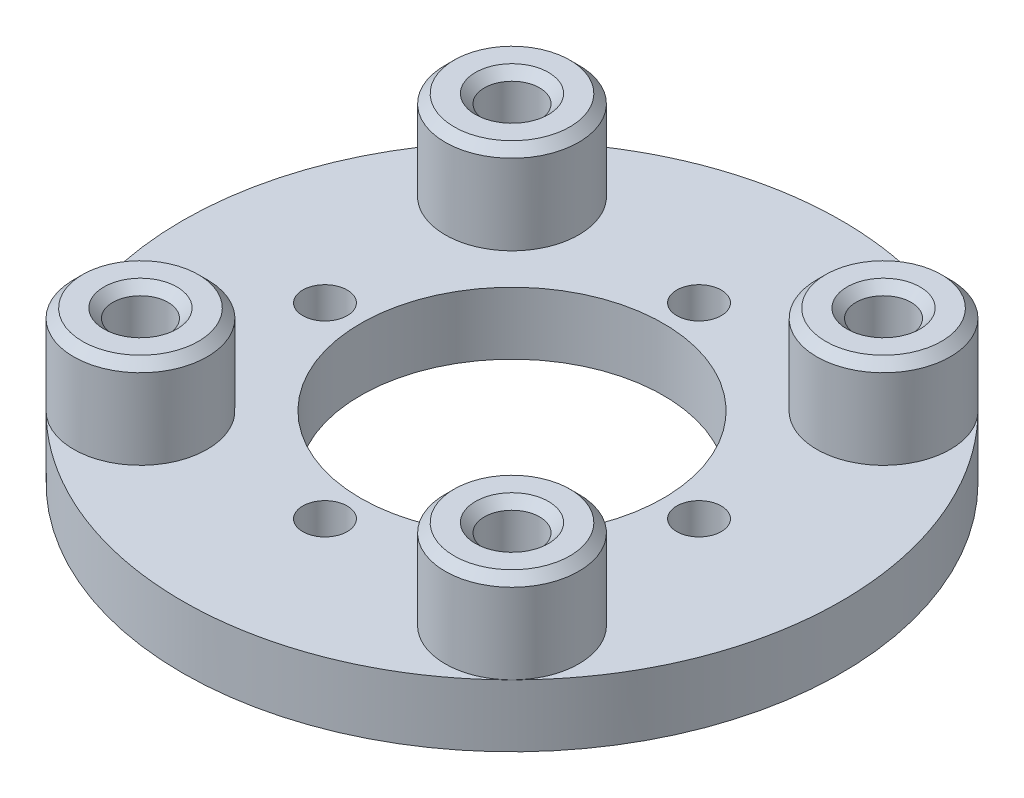
SolidWorks part; units mm, degrees
ref_plane "Front" through (0, 0, 0) normal (0, 0, 1) x (1, 0, 0)
ref_plane "Top" through (0, 0, 0) normal (0, 1, 0) x (1, 0, 0)
ref_plane "Right" through (0, 0, 0) normal (1, 0, 0) x (0, 0, -1)
sketch "草图1" plane through (0, 0, 0) normal (0, 1, 0) x (1, 0, 0)
  circle A0 centre (0, 0) radius 37
  circle A1 centre (21, 0) radius 2.5
  circle A2 centre (0, -21) radius 2.5
  circle A3 centre (-21, 0) radius 2.5
  circle A4 centre (0, 21) radius 2.5
  circle A5 centre (0, 0) radius 17
  point P14 (0, 0)
  dimension "D1" = 74
  dimension "D3" = 5
  dimension "D4" = 34
  dimension "D2" = 21
extrude "凸台-拉伸1" add sketch "草图1" along normal blind 7
sketch "草图2" plane through (0, 0, 0) normal (0, -1, 0) x (1, 0, 0)
  line L0 (0, 0) -> (34.2419, 34.2419) construction
  circle A0 centre (20.8597, 20.8597) radius 3.1
  circle A1 centre (20.8597, -20.8597) radius 3.1
  circle A2 centre (-20.8597, -20.8597) radius 3.1
  circle A3 centre (-20.8597, 20.8597) radius 3.1
  point P14 (0, 0)
  dimension "D1" = 6.2
  dimension "D2" = 29.5
ref_plane "基准面1" through (0, 50, 0) normal (0, 1, 0) x (1, 0, 0)
sketch "草图4" plane through (0, 7, 0) normal (0, 1, 0) x (1, 0, 0)
  circle A0 centre (20.8597, -20.8597) radius 7.5
  circle A2 centre (-20.8597, -20.8597) radius 7.5
  circle A4 centre (-20.8597, 20.8597) radius 7.5
  circle A6 centre (20.8597, 20.8597) radius 7.5
  point P16 (0, 0)
  dimension "D1" = 4
sketch "草图3" plane through (0, 50, 0) normal (0, 1, 0) x (1, 0, 0)
  line L0 (-48.3593, 0) -> (48.1025, 0) construction
  line L1 (-24.5, -24.5) -> (24.5, -24.5)
  line L2 (-24.5, -24.5) -> (-24.5, 24.5)
  line L3 (-24.5, 24.5) -> (24.5, 24.5)
  line L4 (24.5, -24.5) -> (24.5, 24.5)
  line L5 (-24.5, -24.5) -> (24.5, 24.5) construction
  line L6 (-24.5, 24.5) -> (24.5, -24.5) construction
  line L7 (0, 44.9496) -> (0, -39.3078) construction
  circle A0 centre (15.5, 15.5) radius 1.75
  circle A1 centre (0, 0) radius 11.1
  circle A2 centre (15.5, -15.5) radius 1.75
  circle A3 centre (-15.5, -15.5) radius 1.75
  circle A4 centre (-15.5, 15.5) radius 1.75
  point P0 (0, 0)
  point P23 (0, 0)
  dimension "D3" = 3.5
  dimension "D5" = 22.2
  dimension "D1" = 49
  dimension "D2" = 49
  dimension "D4" = 15.5
extrude "凸台-拉伸9" add sketch "草图4" along normal blind 10
extrude "切除-拉伸1" cut sketch "草图2" against normal up to next
chamfer "倒角1" distance 1 angle 45 12 edges at (20.8597, 0, -23.9597) (-20.8597, 0, -23.9597) (-20.8597, 0, 17.7597) (20.8597, 0, 17.7597) (20.8597, 17, -17.7597) (-20.8597, 17, -17.7597) (-20.8597, 17, 23.9597) (20.8597, 17, 23.9597) (20.8597, 17, 28.3597) (20.8597, 17, -13.3597) (-20.8597, 17, -13.3597) (-20.8597, 17, 28.3597)
